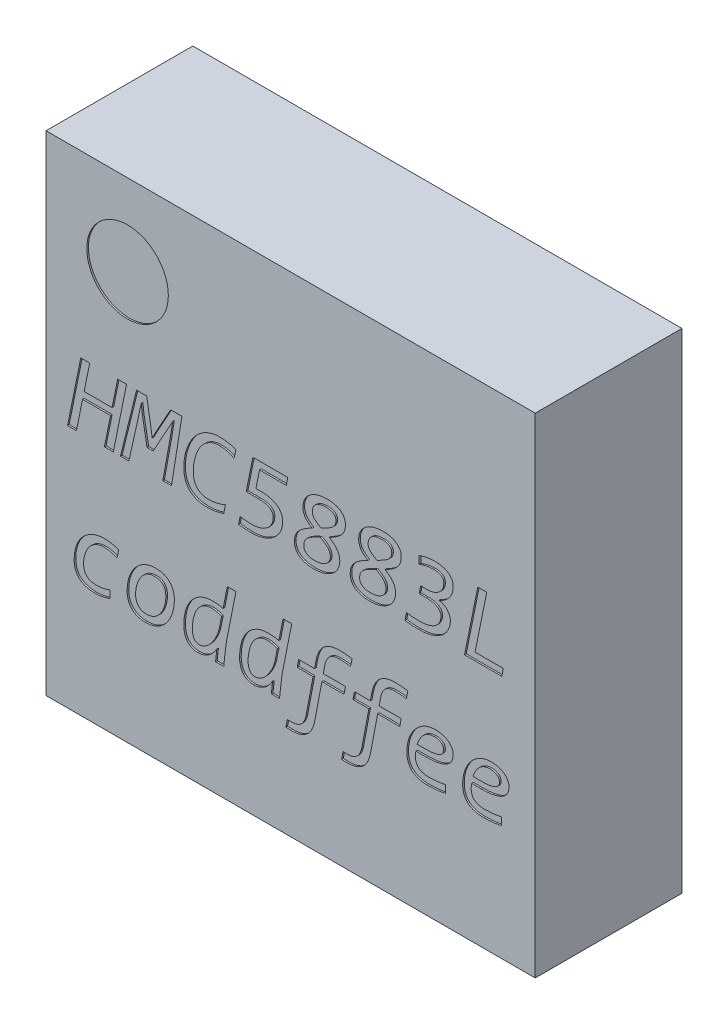
SolidWorks part; units mm, degrees
material "1023 碳钢板 (SS)"
ref_plane "前视基准面" through (0, 0, 0) normal (0, 0, 1) x (1, 0, 0)
ref_plane "上视基准面" through (0, 0, 0) normal (0, 1, 0) x (1, 0, 0)
ref_plane "右视基准面" through (0, 0, 0) normal (1, 0, 0) x (0, 0, -1)
ref_plane "芯片基底面" through (0, 0, 0.01) normal (0, 0, 1) x (1, 0, 0)
sketch "草图1" plane through (0, 0, 0.01) normal (0, 0, 1) x (1, 0, 0)
  line L1 (-1.5, 1.5) -> (1.5, 1.5)
  line L2 (-1.5, 1.5) -> (-1.5, -1.5)
  line L3 (-1.5, -1.5) -> (1.5, -1.5)
  line L4 (1.5, 1.5) -> (1.5, -1.5)
  line L5 (-1.5, 1.5) -> (1.5, -1.5) construction
  line L6 (-1.5, -1.5) -> (1.5, 1.5) construction
  point P0 (0, 0)
extrude "凸台-拉伸1" add sketch "草图1" along normal blind 0.9
sketch "草图3" plane through (0, 0, 0) normal (0, 0, 1) x (1, 0, 0)
  line L0 (1.4625, 0.375) -> (1.1375, 0.375)
  line L1 (1.4625, 0.375) -> (1.4625, 0.125)
  line L2 (1.4625, 0.125) -> (1.1375, 0.125)
  line L3 (1.1375, 0.375) -> (1.1375, 0.125)
  line L4 (1.4625, 0.875) -> (1.1375, 0.875)
  line L5 (1.4625, 0.875) -> (1.4625, 0.625)
  line L6 (1.4625, 0.625) -> (1.1375, 0.625)
  line L7 (1.1375, 0.875) -> (1.1375, 0.625)
  line L8 (1.4625, 0.875) -> (1.1375, 0.625) construction
  line L9 (1.4625, 0.625) -> (1.1375, 0.875) construction
  line L10 (1.4625, 0.375) -> (1.1375, 0.125) construction
  line L11 (1.4625, 0.125) -> (1.1375, 0.375) construction
  line L12 (1.4625, -0.125) -> (1.1375, -0.125)
  line L13 (1.4625, -0.125) -> (1.4625, -0.375)
  line L14 (1.4625, -0.375) -> (1.1375, -0.375)
  line L15 (1.1375, -0.125) -> (1.1375, -0.375)
  line L16 (1.4625, -0.125) -> (1.1375, -0.375) construction
  line L17 (1.4625, -0.375) -> (1.1375, -0.125) construction
  line L18 (1.4625, -0.625) -> (1.1375, -0.625)
  line L19 (1.4625, -0.625) -> (1.4625, -0.875)
  line L20 (1.4625, -0.875) -> (1.1375, -0.875)
  line L21 (1.1375, -0.625) -> (1.1375, -0.875)
  line L22 (1.4625, -0.625) -> (1.1375, -0.875) construction
  line L23 (1.4625, -0.875) -> (1.1375, -0.625) construction
  line L24 (0.375, -1.4625) -> (0.375, -1.1375)
  line L25 (0.375, -1.4625) -> (0.125, -1.4625)
  line L26 (0.125, -1.4625) -> (0.125, -1.1375)
  line L27 (0.375, -1.1375) -> (0.125, -1.1375)
  line L28 (0.875, -1.4625) -> (0.875, -1.1375)
  line L29 (0.875, -1.4625) -> (0.625, -1.4625)
  line L30 (0.625, -1.4625) -> (0.625, -1.1375)
  line L31 (0.875, -1.1375) -> (0.625, -1.1375)
  line L32 (-0.125, -1.4625) -> (-0.125, -1.1375)
  line L33 (-0.125, -1.4625) -> (-0.375, -1.4625)
  line L34 (-0.375, -1.4625) -> (-0.375, -1.1375)
  line L35 (-0.125, -1.1375) -> (-0.375, -1.1375)
  line L36 (-0.625, -1.4625) -> (-0.625, -1.1375)
  line L37 (-0.625, -1.4625) -> (-0.875, -1.4625)
  line L38 (-0.875, -1.4625) -> (-0.875, -1.1375)
  line L39 (-0.625, -1.1375) -> (-0.875, -1.1375)
  line L40 (0.875, -1.4625) -> (0.625, -1.1375) construction
  line L41 (0.625, -1.4625) -> (0.875, -1.1375) construction
  line L42 (0.375, -1.4625) -> (0.125, -1.1375) construction
  line L43 (0.125, -1.4625) -> (0.375, -1.1375) construction
  line L44 (-0.125, -1.4625) -> (-0.375, -1.1375) construction
  line L45 (-0.375, -1.4625) -> (-0.125, -1.1375) construction
  line L46 (-0.625, -1.4625) -> (-0.875, -1.1375) construction
  line L47 (-0.875, -1.4625) -> (-0.625, -1.1375) construction
  line L48 (-1.4625, -0.375) -> (-1.1375, -0.375)
  line L49 (-1.4625, -0.375) -> (-1.4625, -0.125)
  line L50 (-1.4625, -0.125) -> (-1.1375, -0.125)
  line L51 (-1.1375, -0.375) -> (-1.1375, -0.125)
  line L52 (-1.4625, -0.875) -> (-1.1375, -0.875)
  line L53 (-1.4625, -0.875) -> (-1.4625, -0.625)
  line L54 (-1.4625, -0.625) -> (-1.1375, -0.625)
  line L55 (-1.1375, -0.875) -> (-1.1375, -0.625)
  line L56 (-1.4625, 0.125) -> (-1.1375, 0.125)
  line L57 (-1.4625, 0.125) -> (-1.4625, 0.375)
  line L58 (-1.4625, 0.375) -> (-1.1375, 0.375)
  line L59 (-1.1375, 0.125) -> (-1.1375, 0.375)
  line L60 (-1.4625, 0.625) -> (-1.1375, 0.625)
  line L61 (-1.4625, 0.625) -> (-1.4625, 0.875)
  line L62 (-1.4625, 0.875) -> (-1.1375, 0.875)
  line L63 (-1.1375, 0.625) -> (-1.1375, 0.875)
  line L64 (-1.4625, -0.875) -> (-1.1375, -0.625) construction
  line L65 (-1.4625, -0.625) -> (-1.1375, -0.875) construction
  line L66 (-1.4625, -0.375) -> (-1.1375, -0.125) construction
  line L67 (-1.4625, -0.125) -> (-1.1375, -0.375) construction
  line L68 (-1.4625, 0.125) -> (-1.1375, 0.375) construction
  line L69 (-1.4625, 0.375) -> (-1.1375, 0.125) construction
  line L70 (-1.4625, 0.625) -> (-1.1375, 0.875) construction
  line L71 (-1.4625, 0.875) -> (-1.1375, 0.625) construction
  line L72 (-0.375, 1.4625) -> (-0.375, 1.1375)
  line L73 (-0.375, 1.4625) -> (-0.125, 1.4625)
  line L74 (-0.125, 1.4625) -> (-0.125, 1.1375)
  line L75 (-0.375, 1.1375) -> (-0.125, 1.1375)
  line L76 (-0.875, 1.4625) -> (-0.875, 1.1375)
  line L77 (-0.875, 1.4625) -> (-0.625, 1.4625)
  line L78 (-0.625, 1.4625) -> (-0.625, 1.1375)
  line L79 (-0.875, 1.1375) -> (-0.625, 1.1375)
  line L80 (0.125, 1.4625) -> (0.125, 1.1375)
  line L81 (0.125, 1.4625) -> (0.375, 1.4625)
  line L82 (0.375, 1.4625) -> (0.375, 1.1375)
  line L83 (0.125, 1.1375) -> (0.375, 1.1375)
  line L84 (0.625, 1.4625) -> (0.625, 1.1375)
  line L85 (0.625, 1.4625) -> (0.875, 1.4625)
  line L86 (0.875, 1.4625) -> (0.875, 1.1375)
  line L87 (0.625, 1.1375) -> (0.875, 1.1375)
  line L88 (-0.875, 1.4625) -> (-0.625, 1.1375) construction
  line L89 (-0.625, 1.4625) -> (-0.875, 1.1375) construction
  line L90 (-0.375, 1.4625) -> (-0.125, 1.1375) construction
  line L91 (-0.125, 1.4625) -> (-0.375, 1.1375) construction
  line L92 (0.125, 1.4625) -> (0.375, 1.1375) construction
  line L93 (0.375, 1.4625) -> (0.125, 1.1375) construction
  line L94 (0.625, 1.4625) -> (0.875, 1.1375) construction
  line L95 (0.875, 1.4625) -> (0.625, 1.1375) construction
  point P67 (0, 0)
  dimension "D1" = 4
  dimension "D2" = 4
extrude "凸台-拉伸2" add sketch "草图3" along normal blind 0.01
sketch "草图4" plane through (0, 0, 0.91) normal (0, 0, 1) x (1, 0, 0)
  line L0 (-1.5, 0) -> (1.5, 0) construction
  line L2 (-1.5, 1.5) -> (-1.5, -1.5) construction
  line L3 (1.5, -1.5) -> (1.5, 1.5) construction
  line L5 (-1.5, -0.8) -> (1.5, -0.8) construction
  circle A0 centre (-1, 1) radius 0.25
  text T0 "<i>HMC5883L</i>" font "Consolas" height 0.4
  text T1 "<i>coddffee</i>" font "Consolas" height 0.4
extrude "切除-拉伸1" cut sketch "草图4" against normal blind 0.01
